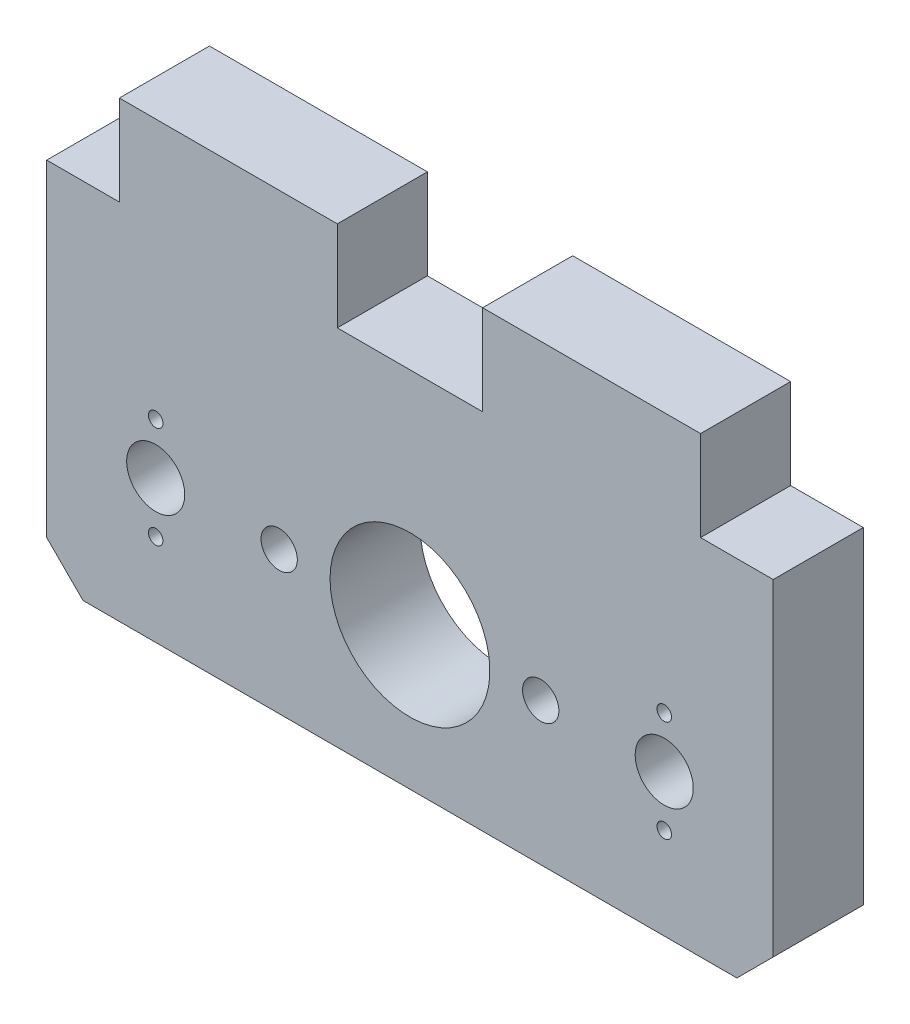
SolidWorks part; units mm, degrees
ref_plane "Front Plane" through (0, 0, 0) normal (0, 0, 1) x (1, 0, 0)
ref_plane "Top Plane" through (0, 0, 0) normal (0, 1, 0) x (1, 0, 0)
ref_plane "Right Plane" through (0, 0, 0) normal (1, 0, 0) x (0, 0, -1)
sketch "Model" plane through (0, 0, 0) normal (0, 0, 1) x (1, 0, 0)
  line L13 (-45, 0) -> (-50, 5)
  line L14 (-45, 0) -> (45, 0)
  line L15 (-50, 5) -> (-50, 50)
  line L16 (-50, 50) -> (-40, 50)
  line L17 (50, 5) -> (50, 50)
  line L18 (45, 0) -> (50, 5)
  line L19 (40, 50) -> (50, 50)
  line L20 (0, 0) -> (0, 50) construction
  line L21 (-40, 50) -> (-40, 62.4)
  line L22 (-40, 62.4) -> (-10, 62.4)
  line L23 (-10, 50) -> (-10, 62.4)
  line L24 (-10, 50) -> (10, 50)
  line L25 (10, 50) -> (10, 62.4)
  line L26 (10, 62.4) -> (40, 62.4)
  line L27 (40, 50) -> (40, 62.4)
  line L28 (50, 19.6) -> (-50, 19.6) construction
  line L29 (-35, 19.6) -> (-35, 26.6) construction
  circle A7 centre (0, 19.6) radius 11
  circle A8 centre (-35, 19.6) radius 4
  circle A9 centre (35, 19.6) radius 4
  circle A10 centre (-35, 26.6) radius 1
  circle A11 centre (-35, 12.6) radius 1
  circle A12 centre (35, 12.6) radius 1
  circle A13 centre (35, 26.6) radius 1
  circle A14 centre (-18, 19.6) radius 2.5
  circle A15 centre (18, 19.6) radius 2.5
  dimension "D19" = 22
  dimension "D22" = 8
  dimension "D26" = 2
  dimension "D32" = 5
  dimension "D4" = 5
  dimension "D5" = 5
  dimension "D6" = 100
  dimension "D8" = 5
  dimension "D10" = 50
  dimension "D12" = 12.4
  dimension "D15" = 30
  dimension "D17" = 10
  dimension "D23" = 15
  dimension "D24" = 30.4
  dimension "D28" = 7
  dimension "D29" = 18
extrude "Boss-Extrude1" add sketch "Model" along normal blind 12.4
equation "\"material-thickness\"= 12.4mm"
equation "\"tab-width-small\"= 20mm ' Width of the small version of the Tab"
equation "\"tab-width-large\"= 30mm ' Width of the large version of the Tab"
equation "\"spindle-thread-height\"= 30.4mm ' Height from the base to the spindle for the stepper motor / Servo"
equation "\"spindle-thread-rbearing-diameter\"= 22mm ' Outer diameter of the rotational bearing"
equation "\"linear-bar-dia\"= 8mm ' Diameter of the metal slide bar used on the X Axis"
equation "\"D1@Boss-Extrude1\" = \"material-thickness\""
equation "\"D12@Model\"=\"material-thickness\""
equation "\"D15@Model\"=\"tab-width-large\""
equation "\"D19@Model\"=\"spindle-thread-rbearing-diameter\""
equation "\"D22@Model\"=\"linear-bar-dia\""
equation "\"D24@Model\"=\"spindle-thread-height\""
